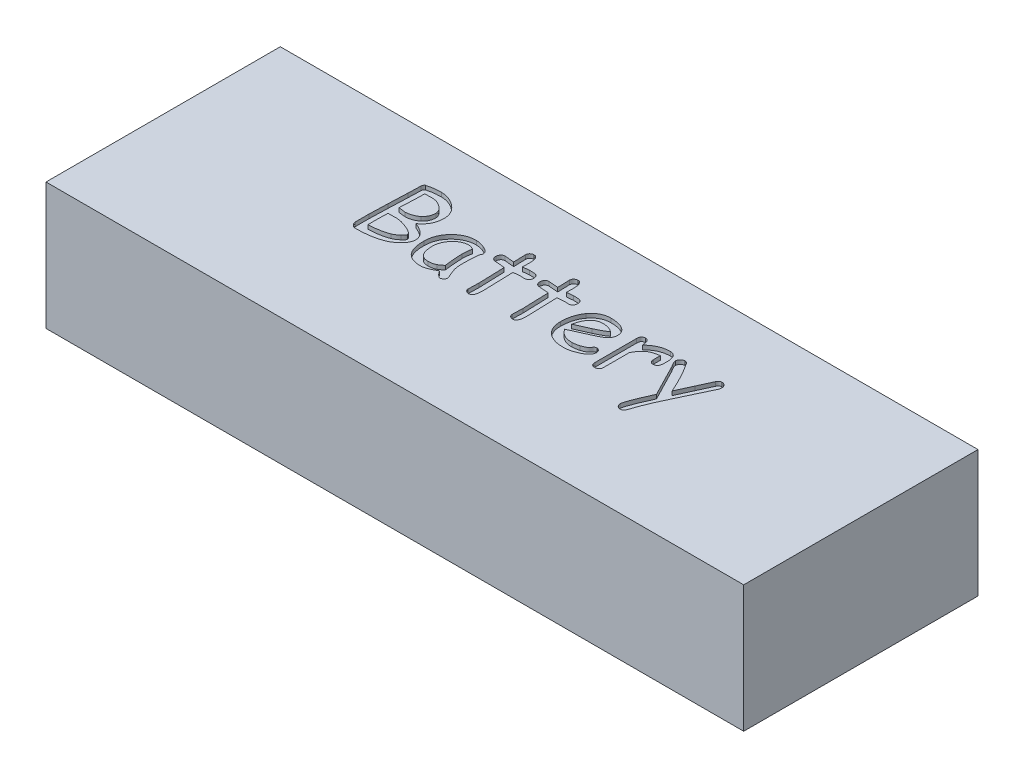
SolidWorks part; units mm, degrees
material "Plain Carbon Steel"
ref_plane "Front" through (0, 0, 0) normal (0, 0, 1) x (1, 0, 0)
ref_plane "Top" through (0, 0, 0) normal (0, 1, 0) x (1, 0, 0)
ref_plane "Right" through (0, 0, 0) normal (1, 0, 0) x (0, 0, -1)
sketch "Sketch1" plane through (0, 0, 0) normal (0, 1, 0) x (1, 0, 0)
  line L1 (-68.453, -22.987) -> (68.453, -22.987)
  line L2 (-68.453, -22.987) -> (-68.453, 22.987)
  line L3 (-68.453, 22.987) -> (68.453, 22.987)
  line L4 (68.453, -22.987) -> (68.453, 22.987)
  line L5 (-68.453, -22.987) -> (68.453, 22.987) construction
  line L6 (-68.453, 22.987) -> (68.453, -22.987) construction
  point P0 (0, 0)
  dimension "D1" = 136.906
  dimension "D2" = 45.974
extrude "Boss-Extrude1" add sketch "Sketch1" along normal blind 24.892
sketch "Sketch2" plane through (0, 24.892, 0) normal (0, 1, 0) x (1, 0, 0)
  line L0 (-111.76, 0) -> (111.76, 0) construction
  text T0 "Battery" font "Comic Sans MS" height in points 48
extrude "Cut-Extrude1" cut sketch "Sketch2" against normal blind 0.7937
